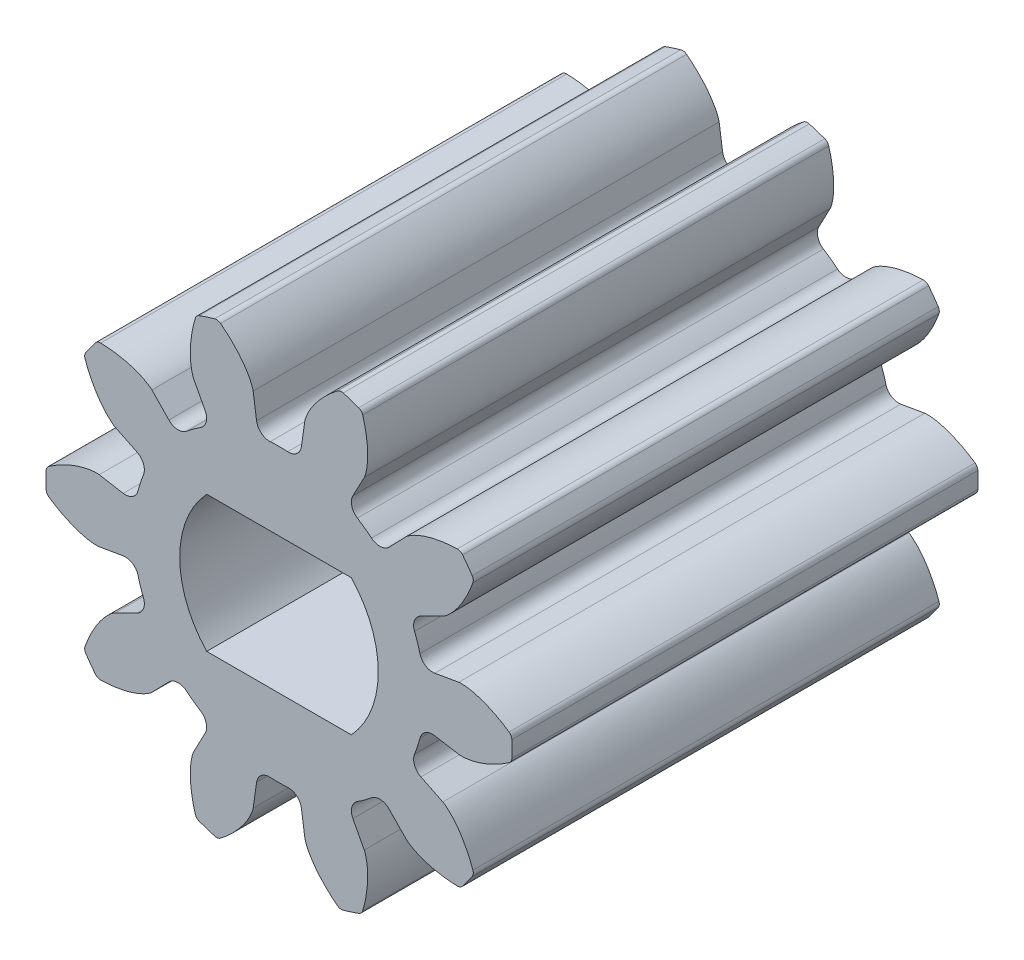
SolidWorks part; units mm, degrees
material "Alloy Steel"
ref_plane "Front" through (0, 0, 0) normal (0, 0, 1) x (1, 0, 0)
ref_plane "Top" through (0, 0, 0) normal (0, 1, 0) x (1, 0, 0)
ref_plane "Right" through (0, 0, 0) normal (1, 0, 0) x (0, 0, -1)
sketch "Sketch1" plane through (0, 0, 0) normal (0, 0, 1) x (1, 0, 0)
  circle A0 centre (0, 0) radius 6.35
extrude "Boss-Extrude1" add sketch "Sketch1" along normal blind 12.7
sketch "Sketch3" plane through (0, 0, 0) normal (0, 0, 1) x (1, 0, 0)
  line L0 (0, 0) -> (43.7181, 0) construction
  line L2 (0, 0) -> (-0.5624, 3.9287) construction
  line L3 (0, 0) -> (0.5624, 3.9287) construction
  line L4 (0.5624, 3.9287) -> (0.7046, 4.9224) construction
  line L5 (0, 0) -> (0, 61.276) construction
  line L6 (-0.5624, 3.9287) -> (-0.7046, 4.9224) construction
  circle A0 centre (0, 0) radius 6.35 construction
  circle A1 centre (0, 0) radius 5.2917 construction
  circle A2 centre (0, 0) radius 4.9725 construction
  arc A3 (0.5624, 3.9287) -> (-0.5624, 3.9287) centre (0, 0) ccw construction
  arc A5 (1.6642, 6.128) -> (-1.6642, 6.128) centre (0, 0) ccw
  spline S0 degree 4 poles (-0.7046, 4.9224) (-0.705, 4.9247) (-0.7061, 4.9311) (-0.7087, 4.9431) (-0.7137, 4.9626) (-0.721, 4.9872) (-0.7316, 5.0187) (-0.7454, 5.0554) (-0.7621, 5.0953) (-0.7818, 5.1381) (-0.8028, 5.1804) (-0.825, 5.2221) (-0.8483, 5.2631) (-0.8779, 5.3122) (-0.9151, 5.3703) (-0.9613, 5.437) (-1.0167, 5.511) (-1.0764, 5.5846) (-1.1378, 5.6556) (-1.2027, 5.7255) (-1.2676, 5.7919) (-1.338, 5.8588) (-1.4044, 5.9196) (-1.4819, 5.9855) (-1.5453, 6.0379) (-1.6323, 6.1046) (-1.6846, 6.1433) (-1.7469, 6.1876) (-1.7752, 6.2068) (-1.7925, 6.2186) knots 0 0 0 0 0 0.005377 0.015084 0.028532 0.04661 0.064855 0.092111 0.119476 0.146842 0.174209 0.201575 0.228941 0.256307 0.307035 0.361767 0.4165 0.471232 0.525964 0.580697 0.635429 0.690161 0.744894 0.799626 0.854358 0.909091 0.954545 1 1 1 1 1 construction
  spline S1 degree 4 poles (-0.7046, 4.9224) (-0.705, 4.9247) (-0.7061, 4.9311) (-0.7087, 4.9431) (-0.7137, 4.9626) (-0.721, 4.9872) (-0.7316, 5.0187) (-0.7454, 5.0554) (-0.7621, 5.0953) (-0.7818, 5.1381) (-0.8028, 5.1804) (-0.825, 5.2221) (-0.8483, 5.2631) (-0.8779, 5.3122) (-0.9151, 5.3703) (-0.9613, 5.437) (-1.0167, 5.511) (-1.0764, 5.5846) (-1.1378, 5.6556) (-1.2027, 5.7255) (-1.2676, 5.7919) (-1.338, 5.8588) (-1.4044, 5.9196) (-1.4819, 5.9855) (-1.5453, 6.0379) (-1.6134, 6.0902) (-1.647, 6.1153) (-1.6642, 6.128) knots 0 0 0 0 0 0.005377 0.015084 0.028532 0.04661 0.064855 0.092111 0.119476 0.146842 0.174209 0.201575 0.228941 0.256307 0.307035 0.361767 0.4165 0.471232 0.525964 0.580697 0.635429 0.690161 0.744894 0.799626 0.854358 0.909091 0.909091 0.909091 0.909091 0.909091
  spline S2 degree 4 poles (0.7046, 4.9224) (0.705, 4.9247) (0.7061, 4.9311) (0.7087, 4.9431) (0.7137, 4.9626) (0.721, 4.9872) (0.7316, 5.0187) (0.7454, 5.0554) (0.7621, 5.0953) (0.7818, 5.1381) (0.8028, 5.1804) (0.825, 5.2221) (0.8483, 5.2631) (0.8779, 5.3122) (0.9151, 5.3703) (0.9613, 5.437) (1.0167, 5.511) (1.0764, 5.5846) (1.1378, 5.6556) (1.2027, 5.7255) (1.2676, 5.7919) (1.338, 5.8588) (1.4044, 5.9196) (1.4819, 5.9855) (1.5453, 6.0379) (1.6323, 6.1046) (1.6846, 6.1433) (1.7469, 6.1876) (1.7752, 6.2068) (1.7925, 6.2186) knots 0 0 0 0 0 0.005377 0.015084 0.028532 0.04661 0.064855 0.092111 0.119476 0.146842 0.174209 0.201575 0.228941 0.256307 0.307035 0.361767 0.4165 0.471232 0.525964 0.580697 0.635429 0.690161 0.744894 0.799626 0.854358 0.909091 0.954545 1 1 1 1 1 construction
  spline S3 degree 4 poles (0.7046, 4.9224) (0.705, 4.9247) (0.7061, 4.9311) (0.7087, 4.9431) (0.7137, 4.9626) (0.721, 4.9872) (0.7316, 5.0187) (0.7454, 5.0554) (0.7621, 5.0953) (0.7818, 5.1381) (0.8028, 5.1804) (0.825, 5.2221) (0.8483, 5.2631) (0.8779, 5.3122) (0.9151, 5.3703) (0.9613, 5.437) (1.0167, 5.511) (1.0764, 5.5846) (1.1378, 5.6556) (1.2027, 5.7255) (1.2676, 5.7919) (1.338, 5.8588) (1.4044, 5.9196) (1.4819, 5.9855) (1.5453, 6.0379) (1.6134, 6.0902) (1.647, 6.1153) (1.6642, 6.128) knots 0 0 0 0 0 0.005377 0.015084 0.028532 0.04661 0.064855 0.092111 0.119476 0.146842 0.174209 0.201575 0.228941 0.256307 0.307035 0.361767 0.4165 0.471232 0.525964 0.580697 0.635429 0.690161 0.744894 0.799626 0.854358 0.909091 0.909091 0.909091 0.909091 0.909091
  point P0 (0, 3.9688)
sketch "DCLTBC" plane through (0, 0, 0) normal (0, 0, 1) x (1, 0, 0)
  line L0 (0, 0) -> (41.04, 0) construction
  line L1 (-0.5624, 3.9287) -> (-0.7046, 4.9224) construction
  line L2 (0.5624, 3.9287) -> (0.7046, 4.9224) construction
  line L3 (-0.5624, 3.9287) -> (-0.7046, 4.9224)
  line L4 (0.5624, 3.9287) -> (0.7046, 4.9224)
  line L5 (0, 0) -> (0, 104.9356) construction
  circle A0 centre (0, 0) radius 6.35
  circle A1 centre (0, 0) radius 5.2917 construction
  circle A2 centre (0, 0) radius 4.9725 construction
  arc A3 (0.5624, 3.9287) -> (-0.5624, 3.9287) centre (0, 0) ccw construction
  arc A4 (0.5624, 3.9287) -> (-0.5624, 3.9287) centre (0, 0) ccw
  spline S0 degree 4 poles (-988.7588, -149.038) (-11.8151, 2.4708) (-0.7866, 4.3496) (-0.6413, 4.6789) (-0.7137, 4.9626) (-0.721, 4.9872) (-0.7316, 5.0187) (-0.7454, 5.0554) (-0.7621, 5.0953) (-0.7818, 5.1381) (-0.8028, 5.1804) (-0.825, 5.2221) (-0.8483, 5.2631) (-0.8779, 5.3122) (-0.9151, 5.3703) (-0.9613, 5.437) (-1.0167, 5.511) (-1.0764, 5.5846) (-1.1378, 5.6556) (-1.2027, 5.7255) (-1.2676, 5.7919) (-1.338, 5.8588) (-1.4044, 5.9196) (-1.4819, 5.9855) (-1.8387, 6.2805) (-3.231, 7.2231) (17.05, -7.85) (-807.2758, 598.5552) knots -0.632257 -0.632257 -0.632257 -0.632257 -0.632257 0.005377 0.015084 0.028532 0.04661 0.064855 0.092111 0.119476 0.146842 0.174209 0.201575 0.228941 0.256307 0.307035 0.361767 0.4165 0.471232 0.525964 0.580697 0.635429 0.690161 0.744894 0.799626 0.854358 1.920904 1.920904 1.920904 1.920904 1.920904 only from (-0.7046, 4.9224) to (-1.6642, 6.128) construction
  spline S1 degree 4 poles (988.7588, -149.038) (11.8151, 2.4708) (0.7866, 4.3496) (0.6413, 4.6789) (0.7137, 4.9626) (0.721, 4.9872) (0.7316, 5.0187) (0.7454, 5.0554) (0.7621, 5.0953) (0.7818, 5.1381) (0.8028, 5.1804) (0.825, 5.2221) (0.8483, 5.2631) (0.8779, 5.3122) (0.9151, 5.3703) (0.9613, 5.437) (1.0167, 5.511) (1.0764, 5.5846) (1.1378, 5.6556) (1.2027, 5.7255) (1.2676, 5.7919) (1.338, 5.8588) (1.4044, 5.9196) (1.4819, 5.9855) (1.8387, 6.2805) (3.231, 7.2231) (-17.05, -7.85) (807.2758, 598.5552) knots -0.632257 -0.632257 -0.632257 -0.632257 -0.632257 0.005377 0.015084 0.028532 0.04661 0.064855 0.092111 0.119476 0.146842 0.174209 0.201575 0.228941 0.256307 0.307035 0.361767 0.4165 0.471232 0.525964 0.580697 0.635429 0.690161 0.744894 0.799626 0.854358 1.920904 1.920904 1.920904 1.920904 1.920904 only from (0.7046, 4.9224) to (1.6642, 6.128) construction
  spline S2 degree 4 poles (-0.7046, 4.9224) (-0.705, 4.9247) (-0.7061, 4.9311) (-0.7087, 4.9431) (-0.7137, 4.9626) (-0.721, 4.9872) (-0.7316, 5.0187) (-0.7454, 5.0554) (-0.7621, 5.0953) (-0.7818, 5.1381) (-0.8028, 5.1804) (-0.825, 5.2221) (-0.8483, 5.2631) (-0.8779, 5.3122) (-0.9151, 5.3703) (-0.9613, 5.437) (-1.0167, 5.511) (-1.0764, 5.5846) (-1.1378, 5.6556) (-1.2027, 5.7255) (-1.2676, 5.7919) (-1.338, 5.8588) (-1.4044, 5.9196) (-1.4819, 5.9855) (-1.5453, 6.0379) (-1.6134, 6.0902) (-1.647, 6.1153) (-1.6642, 6.128) knots 0 0 0 0 0 0.005377 0.015084 0.028532 0.04661 0.064855 0.092111 0.119476 0.146842 0.174209 0.201575 0.228941 0.256307 0.307035 0.361767 0.4165 0.471232 0.525964 0.580697 0.635429 0.690161 0.744894 0.799626 0.854358 0.909091 0.909091 0.909091 0.909091 0.909091
  spline S3 degree 4 poles (0.7046, 4.9224) (0.705, 4.9247) (0.7061, 4.9311) (0.7087, 4.9431) (0.7137, 4.9626) (0.721, 4.9872) (0.7316, 5.0187) (0.7454, 5.0554) (0.7621, 5.0953) (0.7818, 5.1381) (0.8028, 5.1804) (0.825, 5.2221) (0.8483, 5.2631) (0.8779, 5.3122) (0.9151, 5.3703) (0.9613, 5.437) (1.0167, 5.511) (1.0764, 5.5846) (1.1378, 5.6556) (1.2027, 5.7255) (1.2676, 5.7919) (1.338, 5.8588) (1.4044, 5.9196) (1.4819, 5.9855) (1.5453, 6.0379) (1.6134, 6.0902) (1.647, 6.1153) (1.6642, 6.128) knots 0 0 0 0 0 0.005377 0.015084 0.028532 0.04661 0.064855 0.092111 0.119476 0.146842 0.174209 0.201575 0.228941 0.256307 0.307035 0.361767 0.4165 0.471232 0.525964 0.580697 0.635429 0.690161 0.744894 0.799626 0.854358 0.909091 0.909091 0.909091 0.909091 0.909091
extrude "Cut-Extrude-DCLTBC" cut sketch "DCLTBC" along normal through all
fillet "Fillet-Tip-DCLTBC" radius 0.1775 2 edges at (1.6642, 6.128, 6.35) (-1.6642, 6.128, 6.35)
fillet "Fillet-Root-DCLTBC" radius 0.3551 2 edges at (-0.5624, 3.9287, 6.35) (0.5624, 3.9287, 6.35)
pattern_circular "CirPattern-DCLTBC" count 10 over 360 about axis through (0, 0, 12.7) along (0, 0, 1) of "Cut-Extrude-DCLTBC", "Fillet-Tip-DCLTBC", "Fillet-Root-DCLTBC"
sketch "DCGTBC" [suppressed] plane through (0, 0, 0) normal (0, 0, 1) x (1, 0, 0)
  line L0 (0, 0) -> (41.04, 0) construction
  line L1 (-30.3113, 2.6519) -> (0, 0) construction
  line L2 (0, 0) -> (30.3113, 2.6519) construction
  line L3 (0, 0) -> (-16.5124, 0)
  line L5 (0, 0) -> (0, 104.9356) construction
  circle A0 centre (0, 0) radius 32.8083
  circle A1 centre (0, 0) radius 31.75 construction
  circle A2 centre (0, 0) radius 29.8352 construction
  arc A3 (0.3431, 30.4251) -> (-0.3431, 30.4251) centre (0, 0) ccw construction
  arc A11 (30.3113, 2.6519) -> (-30.3113, 2.6519) centre (0, 0) ccw
  spline S4 degree 4 poles (999.5829, -8.5126) (12.0676, 28.1501) (0.4973, 28.7888) (0.2998, 29.3527) (0.3412, 29.9153) (0.346, 29.9661) (0.3537, 30.0318) (0.3643, 30.1091) (0.3778, 30.1941) (0.3944, 30.2865) (0.4126, 30.3786) (0.4324, 30.4705) (0.4535, 30.562) (0.4807, 30.6728) (0.5157, 30.8056) (0.5601, 30.9607) (0.6144, 31.1365) (0.674, 31.3155) (0.7363, 31.4916) (0.8033, 31.6693) (0.871, 31.8411) (0.9455, 32.0194) (1.0164, 32.1839) (1.1005, 32.368) (1.4377, 33.0912) (2.6481, 35.3656) (-11.0441, 8.1022) (453.266, 924.8059) knots -0.610578 -0.610578 -0.610578 -0.610578 -0.610578 0.005377 0.015084 0.028532 0.04661 0.064855 0.092111 0.119476 0.146842 0.174209 0.201575 0.228941 0.256307 0.307035 0.361767 0.4165 0.471232 0.525964 0.580697 0.635429 0.690161 0.744894 0.799626 0.854358 1.756141 1.756141 1.756141 1.756141 1.756141 only from (0.3364, 29.8333) to (1.3018, 32.7825) construction
  spline S5 degree 4 poles (-999.5829, -8.5126) (-12.0676, 28.1501) (-0.4973, 28.7888) (-0.2998, 29.3527) (-0.3412, 29.9153) (-0.346, 29.9661) (-0.3537, 30.0318) (-0.3643, 30.1091) (-0.3778, 30.1941) (-0.3944, 30.2865) (-0.4126, 30.3786) (-0.4324, 30.4705) (-0.4535, 30.562) (-0.4807, 30.6728) (-0.5157, 30.8056) (-0.5601, 30.9607) (-0.6144, 31.1365) (-0.674, 31.3155) (-0.7363, 31.4916) (-0.8033, 31.6693) (-0.871, 31.8411) (-0.9455, 32.0194) (-1.0164, 32.1839) (-1.1005, 32.368) (-1.4377, 33.0912) (-2.6481, 35.3656) (11.0441, 8.1022) (-453.266, 924.8059) knots -0.610578 -0.610578 -0.610578 -0.610578 -0.610578 0.005377 0.015084 0.028532 0.04661 0.064855 0.092111 0.119476 0.146842 0.174209 0.201575 0.228941 0.256307 0.307035 0.361767 0.4165 0.471232 0.525964 0.580697 0.635429 0.690161 0.744894 0.799626 0.854358 1.756141 1.756141 1.756141 1.756141 1.756141 only from (-0.3364, 29.8333) to (-1.3018, 32.7825) construction
  spline S6 degree 4 poles (0.3364, 29.8333) (0.3365, 29.838) (0.3369, 29.8509) (0.3382, 29.8754) (0.3412, 29.9153) (0.346, 29.9661) (0.3537, 30.0318) (0.3643, 30.1091) (0.3778, 30.1941) (0.3944, 30.2865) (0.4126, 30.3786) (0.4324, 30.4705) (0.4535, 30.562) (0.4807, 30.6728) (0.5157, 30.8056) (0.5601, 30.9607) (0.6144, 31.1365) (0.674, 31.3155) (0.7363, 31.4916) (0.8033, 31.6693) (0.871, 31.8411) (0.9455, 32.0194) (1.0164, 32.1839) (1.1005, 32.368) (1.1698, 32.5165) (1.2452, 32.6698) (1.2825, 32.7444) (1.3018, 32.7825) knots 0 0 0 0 0 0.005377 0.015084 0.028532 0.04661 0.064855 0.092111 0.119476 0.146842 0.174209 0.201575 0.228941 0.256307 0.307035 0.361767 0.4165 0.471232 0.525964 0.580697 0.635429 0.690161 0.744894 0.799626 0.854358 0.909091 0.909091 0.909091 0.909091 0.909091
  spline S7 degree 4 poles (-0.3364, 29.8333) (-0.3365, 29.838) (-0.3369, 29.8509) (-0.3382, 29.8754) (-0.3412, 29.9153) (-0.346, 29.9661) (-0.3537, 30.0318) (-0.3643, 30.1091) (-0.3778, 30.1941) (-0.3944, 30.2865) (-0.4126, 30.3786) (-0.4324, 30.4705) (-0.4535, 30.562) (-0.4807, 30.6728) (-0.5157, 30.8056) (-0.5601, 30.9607) (-0.6144, 31.1365) (-0.674, 31.3155) (-0.7363, 31.4916) (-0.8033, 31.6693) (-0.871, 31.8411) (-0.9455, 32.0194) (-1.0164, 32.1839) (-1.1005, 32.368) (-1.1698, 32.5165) (-1.2452, 32.6698) (-1.2825, 32.7444) (-1.3018, 32.7825) knots 0 0 0 0 0 0.005377 0.015084 0.028532 0.04661 0.064855 0.092111 0.119476 0.146842 0.174209 0.201575 0.228941 0.256307 0.307035 0.361767 0.4165 0.471232 0.525964 0.580697 0.635429 0.690161 0.744894 0.799626 0.854358 0.909091 0.909091 0.909091 0.909091 0.909091
  dimension "D1" = 5
  dimension "D2" = 5
extrude "Cut-Extrude-DCGTBC" [suppressed] cut sketch "DCGTBC" along normal through all
fillet "Fillet-Tip-DCGTBC" [suppressed] radius 0.1775
pattern_circular "CirPattern-DCGTBC" [suppressed] count 10 over 360
sketch "Sketch4" plane through (0, 0, 12.7) normal (0, 0, 1) x (1, 0, 0)
  line L0 (-1.9696, 1.8542) -> (1.9696, 1.8542)
  line L1 (-1.9696, -1.8542) -> (1.9696, -1.8542)
  circle A0 centre (0, 0) radius 2.7051
  point P8 (2.3853, -1.2758)
  point P9 (0, 0)
  dimension "D1" = 5.4102
  dimension "D3" = 1.8542
  dimension "D2" = 1.8542
extrude "Cut-Extrude2" cut sketch "Sketch4" against normal through all contours L0 A0 L1
equation "\"DiametralPitch\"= 24'Diametral Pitch"
equation "\"NumTeeth\"= 10'Number of Teeth"
equation "\"PressureAngle\"= 20deg'Pressure Angle"
equation "\"Addendum\"= 1 / \"DiametralPitch\"'Addendum"
equation "\"Dedendum\"= 1.25 / \"DiametralPitch\"'Dedendum"
equation "\"WorkingDepth\"= 2 / \"DiametralPitch\"'Working Depth - here for REF (Not used in building model)"
equation "\"WholeDepth\"= 2.25 / \"DiametralPitch\"'Whole Depth - here for REF (Not used in building model)"
equation "\"Clearance\"= .25 / \"DiametralPitch\"'Clearance"
equation "\"CircularPitch\"= pi / \"DiametralPitch\"'Circular Pitch - here for REF (Not used in building model)"
equation "\"PitchCircle\"= \"NumTeeth\" / \"DiametralPitch\"'Pitch Circle - or - Pitch Diameter"
equation "\"OutsideDiameter\"= ( \"NumTeeth\" + 2 ) / \"DiametralPitch\"'Outside Diameter"
equation "\"Fillet_Root\"= \"Clearance\" * cos ( \"PressureAngle\" ) * tan ( ( 90 + \"PressureAngle\" ) / 2 ) 'Fillet Root"
equation "\"AddendumCircle\"= \"PitchCircle\" + ( 2 * \"Addendum\" )'Addendum Circle - or - Addendum Diameter"
equation "\"DedendumCircle\"= \"PitchCircle\" - ( 2 * \"Dedendum\" )'Dedendum Circle - or - Dedendum Diameter"
equation "\"BaseCircle\"= \"PitchCircle\" * cos ( \"PressureAngle\" )'Base Circle - Base Diameter"
equation "\"PitchAngle\"= 360deg / \"NumTeeth\"'Pitch Angle"
equation "\"Alpha\"= sqr ( \"PitchCircle\" ^ 2 - \"BaseCircle\" ^ 2 ) / \"BaseCircle\" * 180 / PI - \"PressureAngle\"'Alpha - Used for Calculating Beta"
equation "\"Beta\"= ( \"PitchAngle\" / 4 - ( \"Alpha\" - 90 ) )'Beta - Used in definition of the parameters for the parametric equation driven curve"
equation "\"Gamma\"= ( \"PitchAngle\" / 4 - ( \"Alpha\" + 90 ) )'Gamma - Used in definition of the parameters for the parametric equation driven curve"
equation "\"Phi\"= sqr ( ( \"AddendumCircle\" / 2 ) ^ 2 - ( \"BaseCircle\" / 2 ) ^ 2 ) / ( \"BaseCircle\" / 2 )'Phi - Used in definition of the parameters for the parametric equation driven curve"
equation "\"DCGTBC\"= iif ( \"DedendumCircle\" > \"BaseCircle\" , \"unsuppressed\" , \"suppressed\" )'if Dedendum Circle IS GREATER THAN BaseCircle THEN UnsuppressORSuppress FEATURE"
equation "\"DCLTBC\"= iif ( \"DedendumCircle\" - .002 > \"BaseCircle\" , \"suppressed\" , \"unsuppressed\" )'if Dedendum Circle - .002 IS GREATER THAN BaseCircle THEN SuppressORUnsuppress FEATURE"
equation "\"Cut-Extrude-DCGTBC\"= iif ( \"DedendumCircle\" > \"BaseCircle\" , \"unsuppressed\" , \"suppressed\" )'if Dedendum Circle IS GREATER THAN BaseCircle THEN UnsuppressORSuppress FEATURE"
equation "\"Cut-Extrude-DCLTBC\"= iif ( \"DedendumCircle\" - .002 > \"BaseCircle\" , \"suppressed\" , \"unsuppressed\" )'if Dedendum Circle - .002 IS GREATER THAN BaseCircle THEN SuppressORUnsuppress FEATURE"
equation "\"CirPattern-DCGTBC\"= iif ( \"DedendumCircle\" > \"BaseCircle\" , \"unsuppressed\" , \"suppressed\" )'if Dedendum Circle IS GREATER THAN BaseCircle THEN UnsuppressORSuppress FEATURE"
equation "\"CirPattern-DCLTBC\"= iif ( \"DedendumCircle\" - .002 > \"BaseCircle\" , \"suppressed\" , \"unsuppressed\" )'if Dedendum Circle - .002 IS GREATER THAN BaseCircle THEN SuppressORUnsuppress FEATURE"
equation "\"Fillet-Tip-DCGTBC\"= iif ( \"DedendumCircle\" > \"BaseCircle\" , \"unsuppressed\" , \"suppressed\" )'if Dedendum Circle IS GREATER THAN BaseCircle THEN UnsuppressORSuppress FEATURE"
equation "\"Fillet-Tip-DCLTBC\"= iif ( \"DedendumCircle\" - .002 > \"BaseCircle\" , \"suppressed\" , \"unsuppressed\" )'if Dedendum Circle - .002 IS GREATER THAN BaseCircle THEN SuppressORUnsuppress FEATURE"
equation "\"Fillet-Root-DCLTBC\"= iif ( \"DedendumCircle\" - .002 > \"BaseCircle\" , \"suppressed\" , \"unsuppressed\" )'if Dedendum Circle - .002 IS GREATER THAN BaseCircle THEN SuppressORUnsuppress FEATURE"
equation "\"D1@CirPattern-DCGTBC\"= \"NumTeeth\"'Number of Teeth"
equation "\"D1@CirPattern-DCLTBC\"= \"NumTeeth\"'Number of Teeth"
equation "\"D1@Fillet-Tip-DCGTBC\"= \"Fillet_Root\" / 2 'Tip Rad For Large No of Teeth"
equation "\"D1@Fillet-Tip-DCLTBC\"=\"Fillet_Root\" / 2'Tip Rad For Small No of Teeth"
equation "\"D1@Fillet-Root-DCLTBC\"= \"Fillet_Root\"'Fillet Root"
